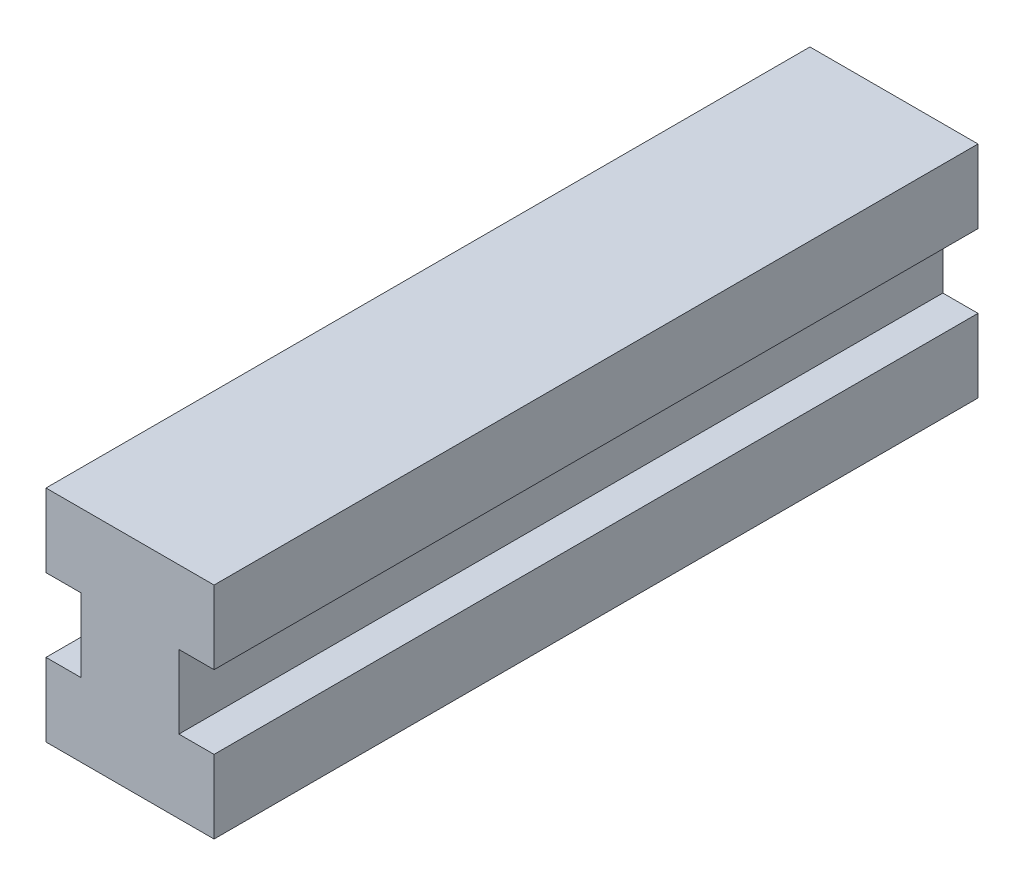
SolidWorks part; units mm, degrees
material "Nylon 101"
ref_plane "Front" through (0, 0, 0) normal (0, 0, 1) x (1, 0, 0)
ref_plane "Top" through (0, 0, 0) normal (0, 1, 0) x (1, 0, 0)
ref_plane "Right" through (0, 0, 0) normal (1, 0, 0) x (0, 0, -1)
sketch "Sketch1" plane through (0, 0, 0) normal (0, 0, 1) x (1, 0, 0)
  line L0 (-2.75, 0) -> (2.75, 0)
  line L1 (2.75, 0) -> (2.75, 2.4)
  line L2 (-2.75, 0) -> (-2.75, 2.4)
  line L3 (0, 0) -> (0, 7.2) construction
  line L4 (-1.6, 3.6) -> (1.6, 3.6) construction
  line L5 (-1.6, 4.8) -> (-1.6, 2.4)
  line L6 (-1.6, 2.4) -> (-2.75, 2.4)
  line L7 (1.6, 4.8) -> (1.6, 2.4)
  line L8 (2.75, 2.4) -> (1.6, 2.4)
  line L15 (-2.75, 7.2) -> (-2.75, 4.8)
  line L16 (2.75, 7.2) -> (2.75, 4.8)
  line L17 (1.6, 4.8) -> (2.75, 4.8)
  line L18 (-2.75, 4.8) -> (-1.6, 4.8)
  line L23 (-2.75, 7.2) -> (2.75, 7.2)
  point P4 (0, 0)
  point P11 (0, 3.6)
  point P14 (0, 3.6)
  dimension "D1" = 5.5
  dimension "D2" = 2.4
  dimension "D3" = 3.2
  dimension "1.2" = 1.2
extrude "Boss-Extrude1" add sketch "Sketch1" along normal blind 25
